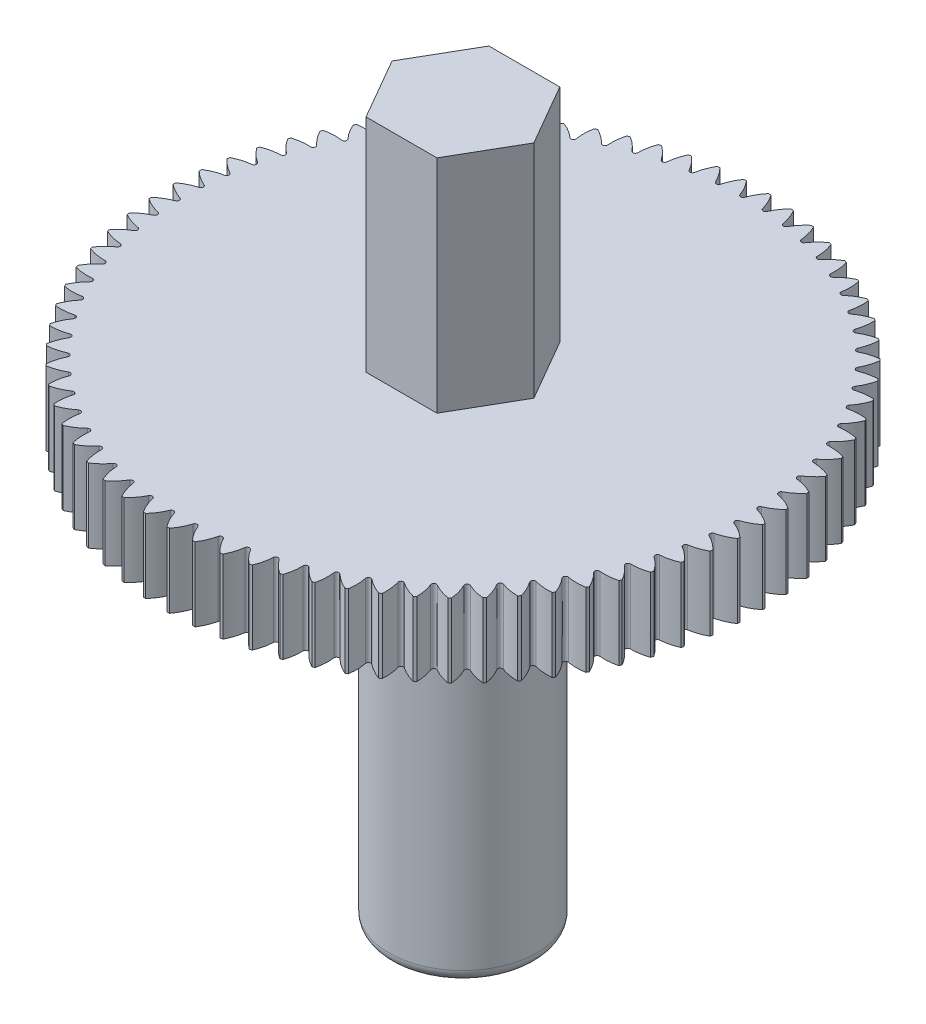
SolidWorks part; units mm, degrees
ref_plane "Front Plane" through (0, 0, 0) normal (0, 0, 1) x (1, 0, 0)
ref_plane "Top Plane" through (0, 0, 0) normal (0, 1, 0) x (1, 0, 0)
ref_plane "Right Plane" through (0, 0, 0) normal (1, 0, 0) x (0, 0, -1)
sketch "Sketch1" plane through (0, 0, 0) normal (0, 0, 1) x (1, 0, 0)
  line L0 (0, 0) -> (0, 29)
  line L1 (0, 0) -> (3, 0)
  line L2 (3, 0) -> (3, 17)
  line L3 (3, 17) -> (12, 17)
  line L4 (12, 17) -> (12, 20)
  line L5 (12, 20) -> (3, 20)
  line L6 (3, 20) -> (3, 29)
  line L7 (3, 29) -> (0, 29)
  dimension "D1" = 29
  dimension "D2" = 3
  dimension "D3" = 17
  dimension "D4" = 9
  dimension "D5" = 3
  dimension "D6" = 9
revolve "Revolve1" add sketch "Sketch1" angle 360 about L0
fillet "Fillet1" radius 0.5 1 edges at (0, 0, -3)
sketch "Sketch2" plane through (0, 29, 0) normal (0, 1, 0) x (1, 0, 0)
  line L1 (1.4434, -2.5) -> (2.8868, 0)
  line L2 (2.8868, 0) -> (1.4434, 2.5)
  line L3 (1.4434, 2.5) -> (-1.4434, 2.5)
  line L4 (-1.4434, 2.5) -> (-2.8868, 0)
  line L5 (-2.8868, 0) -> (-1.4434, -2.5)
  line L6 (-1.4434, -2.5) -> (1.4434, -2.5)
  circle A0 centre (0, 0) radius 3 construction
  circle A1 centre (0, 0) radius 3
  circle A2 centre (0, 0) radius 2.5 construction
  dimension "D1" = 5
  dimension "D2" = 2.8868
extrude "Cut-Extrude1" cut sketch "Sketch2" against normal blind 9
sketch "Sketch3" plane through (0, 20, 0) normal (0, 1, 0) x (1, 0, 0)
  line L0 (0, 0) -> (0, 19.1674) construction
  circle A0 centre (0, 0) radius 12 construction
  arc A1 (0.45, 11.9916) -> (-0.45, 11.9916) centre (0, 0) ccw
  arc A2 (-0.45, 11.9916) -> (-0.0942, 11.3714) centre (-1.979, 10.7023) cw
  arc A3 (0.0942, 11.3714) -> (0.45, 11.9916) centre (1.979, 10.7023) cw
  arc A4 (-0.0942, 11.3714) -> (0.0942, 11.3714) centre (0, 11.4049) ccw
  point P11 (0, 10.9916)
  dimension "D2" = 2
  dimension "D3" = 2
  dimension "D5" = 0.1
  dimension "D1" = 0.9
  dimension "D4" = 1
extrude "Cut-Extrude2" cut sketch "Sketch3" against normal blind 4
pattern_circular "CirPattern1" count 75 over 360 about axis through (0, 0, 0) along (0, 1, 0) of "Cut-Extrude2"
